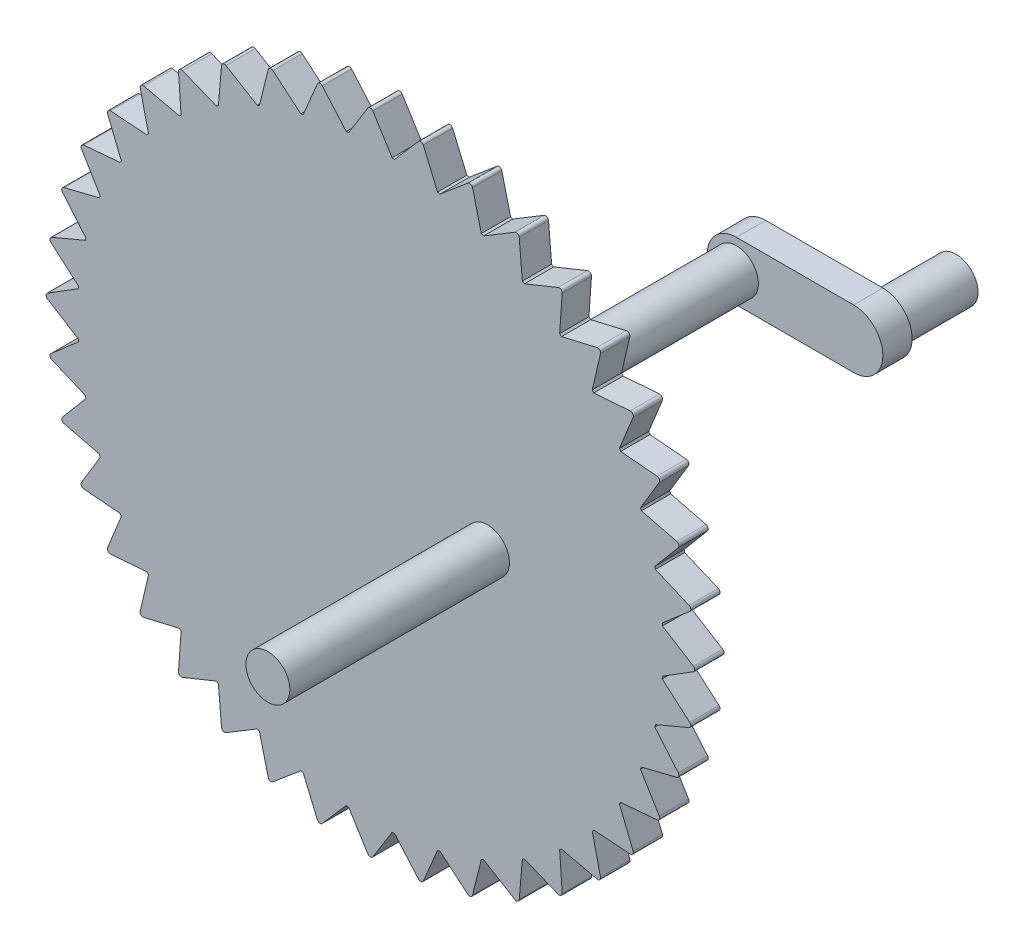
SolidWorks part; units mm, degrees
ref_plane "Front Plane" through (0, 0, 0) normal (0, 0, 1) x (1, 0, 0)
ref_plane "Top Plane" through (0, 0, 0) normal (0, 1, 0) x (1, 0, 0)
ref_plane "Right Plane" through (0, 0, 0) normal (1, 0, 0) x (0, 0, -1)
sketch "Sketch1" plane through (0, 0, 0) normal (0, 0, 1) x (1, 0, 0)
  circle A0 centre (0, 0) radius 20
  dimension "D1" = 40
extrude "Boss-Extrude1" add sketch "Sketch1" along normal blind 2
sketch "Sketch2" plane through (0, 0, 2) normal (0, 0, 1) x (1, 0, 0)
  line L0 (0, 22.5839) -> (0, 14.6261) construction
  line L1 (-0.1697, 22.0573) -> (-1.4864, 19.9447)
  line L2 (-1.4864, 19.9447) -> (-0.1697, 22.0573)
  line L3 (0.1697, 22.0573) -> (1.4864, 19.9447)
  circle A0 centre (0, 0) radius 20 construction
  arc A1 (2.238, 19.8744) -> (-1.4864, 19.9447) centre (0, 0) ccw
  circle A2 centre (0, 0) radius 20
  arc A3 (-0.1697, 22.0573) -> (0.1697, 22.0573) centre (0, 21.9515) cw
  circle A5 centre (0, 0) radius 20
  circle A6 centre (0, 0) radius 20
  dimension "D1" = 0.2
  dimension "D2" = 0
extrude "Boss-Extrude2" add sketch "Sketch2" against normal up to surface (2 mm away) up to face at (20, 0, 0)
pattern_circular "CirPattern1" count 40 every 9 about axis through (0, 0, 0) along (0, 0, 1) of "Boss-Extrude2"
sketch "Sketch3" plane through (0, 0, 2) normal (0, 0, 1) x (1, 0, 0)
  circle A0 centre (0, 0) radius 1.5
  dimension "D1" = 3
extrude "Boss-Extrude3" add sketch "Sketch3" against normal blind 25
sketch "Sketch4" plane through (0, 0, 2) normal (0, 0, 1) x (1, 0, 0)
  line L0 (0, -1.8288) -> (0, 3.0029) construction
  circle A0 centre (-8, 0) radius 1.5
  circle A1 centre (8, 0) radius 1.5
  dimension "D2" = 3
  dimension "D1" = 8
extrude "Boss-Extrude4" add sketch "Sketch4" along normal blind 15
sketch "Sketch6" plane through (0, 0, -23) normal (0, 0, -1) x (-1, 0, 0)
  line L0 (0, 0) -> (-8, 0) construction
  line L1 (0, -2) -> (-8, -2)
  line L2 (0, 2) -> (-8, 2)
  arc A0 (0, -2) -> (0, 2) centre (0, 0) ccw
  arc A1 (-8, 2) -> (-8, -2) centre (-8, 0) ccw
  point P3 (-4, 0)
  dimension "D2" = 2
  dimension "D1" = 8
extrude "Boss-Extrude5" add sketch "Sketch6" along normal blind 2
sketch "Sketch7" plane through (0, 0, -25) normal (0, 0, -1) x (-1, 0, 0)
  circle A0 centre (-8, 0) radius 1.5
  arc A1 (-8, 2) -> (-8, -2) centre (-8, 0) ccw construction
  dimension "D1" = 3
extrude "Boss-Extrude6" add sketch "Sketch7" along normal blind 5
sketch "Sketch8" plane through (0, 0, 17) normal (0, 0, 1) x (1, 0, 0)
  circle A1 centre (-8, 0) radius 1.5
  circle A2 centre (-8, 0) radius 1.5
  dimension "D1" = 0
extrude "Cut-Extrude1" cut sketch "Sketch8" against normal up to surface (15 mm away) up to face at (-6.5, 0, 2)
